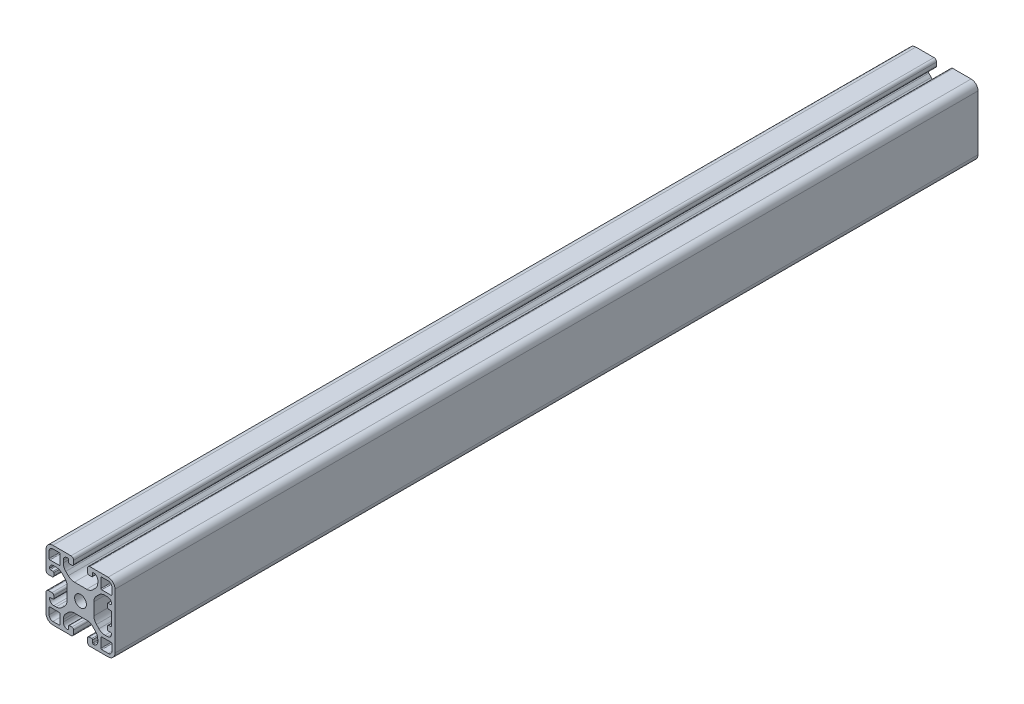
SolidWorks part; units mm, degrees
ref_plane "Piano frontale" through (0, 0, 0) normal (0, 0, 1) x (1, 0, 0)
ref_plane "Piano superiore" through (0, 0, 0) normal (0, 1, 0) x (1, 0, 0)
ref_plane "Piano destro" through (0, 0, 0) normal (1, 0, 0) x (0, 0, -1)
ref_plane "Piano1" through (0, 0, -340) normal (0, 0, -1) x (-1, 0, 0)
sketch "Schizzo1" plane through (0, 0, -340) normal (0, 0, -1) x (-1, 0, 0)
  line L0 (-12.3, -18.2) -> (-16, -18.2)
  line L1 (-18.2, -16) -> (-18.2, -12.3)
  line L2 (-17.7, -11.8) -> (-12.3, -11.8)
  line L3 (-11.8, -12.3) -> (-11.8, -17.7)
  line L4 (-11.8, 17.7) -> (-11.8, 12.3)
  line L5 (-12.3, 11.8) -> (-17.7, 11.8)
  line L6 (-18.2, 12.3) -> (-18.2, 16)
  line L7 (-16, 18.2) -> (-12.3, 18.2)
  line L8 (18.2, 16) -> (18.2, 12.3)
  line L9 (17.7, 11.8) -> (12.3, 11.8)
  line L10 (11.8, 12.3) -> (11.8, 17.7)
  line L11 (12.3, 18.2) -> (16, 18.2)
  line L12 (6.5, -15.5) -> (5, -15.5)
  line L13 (4, -16.5) -> (4, -18.5)
  line L14 (5.5, -20) -> (16, -20)
  line L15 (20, -16) -> (20, -5.5)
  line L16 (18.5, -4) -> (16.5, -4)
  line L17 (15.5, -5) -> (15.5, -6.5)
  line L18 (16, -7) -> (17.55, -7)
  line L19 (18, -7.45) -> (18, -7.5)
  line L20 (15.5, -10) -> (14.1924, -10)
  line L21 (10.6569, -8.5355) -> (9.2145, -7.0931)
  line L22 (7.75, -3.5576) -> (7.75, 3.5576)
  line L23 (9.2145, 7.0931) -> (10.6569, 8.5355)
  line L24 (14.1924, 10) -> (15.5, 10)
  line L25 (18, 7.5) -> (18, 7.45)
  line L26 (17.55, 7) -> (16, 7)
  line L27 (15.5, 6.5) -> (15.5, 5)
  line L28 (16.5, 4) -> (18.5, 4)
  line L29 (20, 5.5) -> (20, 16)
  line L30 (16, 20) -> (5.5, 20)
  line L31 (4, 18.5) -> (4, 16.5)
  line L32 (5, 15.5) -> (6.5, 15.5)
  line L33 (7, 16) -> (7, 17.55)
  line L34 (7.45, 18) -> (7.5, 18)
  line L35 (10, 15.5) -> (10, 14.1924)
  line L36 (8.5355, 10.6569) -> (7.0931, 9.2145)
  line L37 (3.5576, 7.75) -> (-3.5576, 7.75)
  line L38 (-7.0931, 9.2145) -> (-8.5355, 10.6569)
  line L39 (-10, 14.1924) -> (-10, 15.5)
  line L40 (-7.5, 18) -> (-7.45, 18)
  line L41 (-7, 17.55) -> (-7, 16)
  line L42 (-6.5, 15.5) -> (-5, 15.5)
  line L43 (-4, 16.5) -> (-4, 18.5)
  line L44 (-5.5, 20) -> (-16, 20)
  line L45 (-20, 16) -> (-20, -16)
  line L46 (-16, -20) -> (-5.5, -20)
  line L47 (-4, -18.5) -> (-4, -16.5)
  line L48 (-5, -15.5) -> (-6.5, -15.5)
  line L49 (-7, -16) -> (-7, -17.55)
  line L50 (-7.45, -18) -> (-7.5, -18)
  line L51 (-10, -15.5) -> (-10, -14.1924)
  line L52 (-8.5355, -10.6569) -> (-7.0931, -9.2145)
  line L53 (-3.5576, -7.75) -> (3.5576, -7.75)
  line L54 (7.0931, -9.2145) -> (8.5355, -10.6569)
  line L55 (10, -14.1924) -> (10, -15.5)
  line L56 (7.5, -18) -> (7.45, -18)
  line L57 (7, -17.55) -> (7, -16)
  line L58 (18.2, -12.3) -> (18.2, -16)
  line L59 (16, -18.2) -> (12.3, -18.2)
  line L60 (11.8, -17.7) -> (11.8, -12.3)
  line L61 (12.3, -11.8) -> (17.7, -11.8)
  line L62 (-16, 7) -> (-17.5, 7)
  line L63 (-15.5, 10) -> (-14.1924, 10)
  line L64 (-10.6569, 8.5355) -> (-9.2145, 7.0931)
  line L65 (-7.75, 3.5576) -> (-7.75, -3.5576)
  line L66 (-9.2145, -7.0931) -> (-10.6569, -8.5355)
  line L67 (-14.1924, -10) -> (-15.5, -10)
  line L68 (-17.5, -7) -> (-16, -7)
  line L69 (-15.5, -6.5) -> (-15.5, -5)
  line L70 (-16.5, -4) -> (-17.5, -4)
  line L71 (-18, -3.5) -> (-18, 3.5)
  line L72 (-17.5, 4) -> (-16.5, 4)
  line L73 (-15.5, 5) -> (-15.5, 6.5)
  arc A0 (-16, -18.2) -> (-18.2, -16) centre (-16, -16) cw
  arc A1 (-18.2, -12.3) -> (-17.7, -11.8) centre (-17.7, -12.3) cw
  arc A2 (-12.3, -11.8) -> (-11.8, -12.3) centre (-12.3, -12.3) cw
  arc A3 (-11.8, -17.7) -> (-12.3, -18.2) centre (-12.3, -17.7) cw
  arc A4 (-12.3, 18.2) -> (-11.8, 17.7) centre (-12.3, 17.7) cw
  arc A5 (-11.8, 12.3) -> (-12.3, 11.8) centre (-12.3, 12.3) cw
  arc A6 (-17.7, 11.8) -> (-18.2, 12.3) centre (-17.7, 12.3) cw
  arc A7 (-18.2, 16) -> (-16, 18.2) centre (-16, 16) cw
  arc A8 (16, 18.2) -> (18.2, 16) centre (16, 16) cw
  arc A9 (18.2, 12.3) -> (17.7, 11.8) centre (17.7, 12.3) cw
  arc A10 (12.3, 11.8) -> (11.8, 12.3) centre (12.3, 12.3) cw
  arc A11 (11.8, 17.7) -> (12.3, 18.2) centre (12.3, 17.7) cw
  arc A12 (5, -15.5) -> (4, -16.5) centre (5, -16.5) ccw
  arc A13 (4, -18.5) -> (5.5, -20) centre (5.5, -18.5) ccw
  arc A14 (16, -20) -> (20, -16) centre (16, -16) ccw
  arc A15 (20, -5.5) -> (18.5, -4) centre (18.5, -5.5) ccw
  arc A16 (16.5, -4) -> (15.5, -5) centre (16.5, -5) ccw
  arc A17 (15.5, -6.5) -> (16, -7) centre (16, -6.5) ccw
  arc A18 (17.55, -7) -> (18, -7.45) centre (17.55, -7.45) cw
  arc A19 (18, -7.5) -> (15.5, -10) centre (15.5, -7.5) cw
  arc A20 (14.1924, -10) -> (10.6569, -8.5355) centre (14.1924, -5) cw
  arc A21 (9.2145, -7.0931) -> (7.75, -3.5576) centre (12.75, -3.5576) cw
  arc A22 (7.75, 3.5576) -> (9.2145, 7.0931) centre (12.75, 3.5576) cw
  arc A23 (10.6569, 8.5355) -> (14.1924, 10) centre (14.1924, 5) cw
  arc A24 (15.5, 10) -> (18, 7.5) centre (15.5, 7.5) cw
  arc A25 (18, 7.45) -> (17.55, 7) centre (17.55, 7.45) cw
  arc A26 (16, 7) -> (15.5, 6.5) centre (16, 6.5) ccw
  arc A27 (15.5, 5) -> (16.5, 4) centre (16.5, 5) ccw
  arc A28 (18.5, 4) -> (20, 5.5) centre (18.5, 5.5) ccw
  arc A29 (20, 16) -> (16, 20) centre (16, 16) ccw
  arc A30 (5.5, 20) -> (4, 18.5) centre (5.5, 18.5) ccw
  arc A31 (4, 16.5) -> (5, 15.5) centre (5, 16.5) ccw
  arc A32 (6.5, 15.5) -> (7, 16) centre (6.5, 16) ccw
  arc A33 (7, 17.55) -> (7.45, 18) centre (7.45, 17.55) cw
  arc A34 (7.5, 18) -> (10, 15.5) centre (7.5, 15.5) cw
  arc A35 (10, 14.1924) -> (8.5355, 10.6569) centre (5, 14.1924) cw
  arc A36 (7.0931, 9.2145) -> (3.5576, 7.75) centre (3.5576, 12.75) cw
  arc A37 (-3.5576, 7.75) -> (-7.0931, 9.2145) centre (-3.5576, 12.75) cw
  arc A38 (-8.5355, 10.6569) -> (-10, 14.1924) centre (-5, 14.1924) cw
  arc A39 (-10, 15.5) -> (-7.5, 18) centre (-7.5, 15.5) cw
  arc A40 (-7.45, 18) -> (-7, 17.55) centre (-7.45, 17.55) cw
  arc A41 (-7, 16) -> (-6.5, 15.5) centre (-6.5, 16) ccw
  arc A42 (-5, 15.5) -> (-4, 16.5) centre (-5, 16.5) ccw
  arc A43 (-4, 18.5) -> (-5.5, 20) centre (-5.5, 18.5) ccw
  arc A44 (-16, 20) -> (-20, 16) centre (-16, 16) ccw
  arc A45 (-20, -16) -> (-16, -20) centre (-16, -16) ccw
  arc A46 (-5.5, -20) -> (-4, -18.5) centre (-5.5, -18.5) ccw
  arc A47 (-4, -16.5) -> (-5, -15.5) centre (-5, -16.5) ccw
  arc A48 (-6.5, -15.5) -> (-7, -16) centre (-6.5, -16) ccw
  arc A49 (-7, -17.55) -> (-7.45, -18) centre (-7.45, -17.55) cw
  arc A50 (-7.5, -18) -> (-10, -15.5) centre (-7.5, -15.5) cw
  arc A51 (-10, -14.1924) -> (-8.5355, -10.6569) centre (-5, -14.1924) cw
  arc A52 (-7.0931, -9.2145) -> (-3.5576, -7.75) centre (-3.5576, -12.75) cw
  arc A53 (3.5576, -7.75) -> (7.0931, -9.2145) centre (3.5576, -12.75) cw
  arc A54 (8.5355, -10.6569) -> (10, -14.1924) centre (5, -14.1924) cw
  arc A55 (10, -15.5) -> (7.5, -18) centre (7.5, -15.5) cw
  arc A56 (7.45, -18) -> (7, -17.55) centre (7.45, -17.55) cw
  arc A57 (7, -16) -> (6.5, -15.5) centre (6.5, -16) ccw
  arc A58 (17.7, -11.8) -> (18.2, -12.3) centre (17.7, -12.3) cw
  arc A59 (18.2, -16) -> (16, -18.2) centre (16, -16) cw
  arc A60 (12.3, -18.2) -> (11.8, -17.7) centre (12.3, -17.7) cw
  arc A61 (11.8, -12.3) -> (12.3, -11.8) centre (12.3, -12.3) cw
  circle A62 centre (0, 0) radius 3.4
  arc A63 (-15.5, 6.5) -> (-16, 7) centre (-16, 6.5) ccw
  arc A64 (-17.5, 7) -> (-18, 7.5) centre (-17.5, 7.5) cw
  arc A65 (-18, 7.5) -> (-15.5, 10) centre (-15.5, 7.5) cw
  arc A66 (-14.1924, 10) -> (-10.6569, 8.5355) centre (-14.1924, 5) cw
  arc A67 (-9.2145, 7.0931) -> (-7.75, 3.5576) centre (-12.75, 3.5576) cw
  arc A68 (-7.75, -3.5576) -> (-9.2145, -7.0931) centre (-12.75, -3.5576) cw
  arc A69 (-10.6569, -8.5355) -> (-14.1924, -10) centre (-14.1924, -5) cw
  arc A70 (-15.5, -10) -> (-18, -7.5) centre (-15.5, -7.5) cw
  arc A71 (-18, -7.5) -> (-17.5, -7) centre (-17.5, -7.5) cw
  arc A72 (-16, -7) -> (-15.5, -6.5) centre (-16, -6.5) ccw
  arc A73 (-15.5, -5) -> (-16.5, -4) centre (-16.5, -5) ccw
  arc A74 (-17.5, -4) -> (-18, -3.5) centre (-17.5, -3.5) cw
  arc A75 (-18, 3.5) -> (-17.5, 4) centre (-17.5, 3.5) cw
  arc A76 (-16.5, 4) -> (-15.5, 5) centre (-16.5, 5) ccw
extrude "Estrusione-Estrusione1" add sketch "Schizzo1" against normal blind 500
